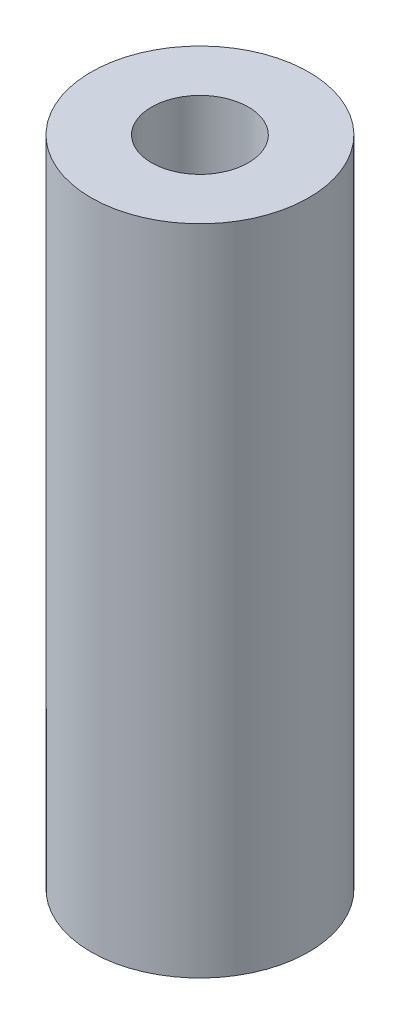
SolidWorks part; units mm, degrees
ref_plane "Front Plane" through (0, 0, 0) normal (0, 0, 1) x (1, 0, 0)
ref_plane "Top Plane" through (0, 0, 0) normal (0, 1, 0) x (1, 0, 0)
ref_plane "Right Plane" through (0, 0, 0) normal (1, 0, 0) x (0, 0, -1)
sketch "Sketch1" plane through (0, 0, 0) normal (0, 1, 0) x (1, 0, 0)
  circle A0 centre (0, 0) radius 4.5
  circle A1 centre (0, 0) radius 2
extrude "Boss-Extrude1" add sketch "Sketch1" along normal blind 27
